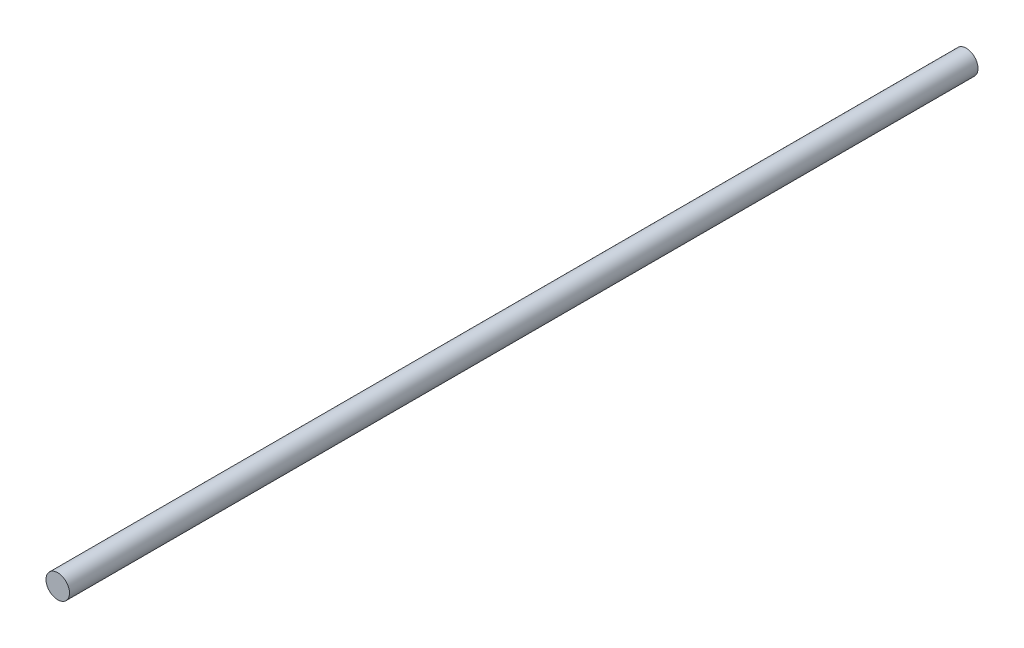
SolidWorks part; units mm, degrees
ref_plane "前视基准面" through (0, 0, 0) normal (0, 0, 1) x (1, 0, 0)
ref_plane "上视基准面" through (0, 0, 0) normal (0, 1, 0) x (1, 0, 0)
ref_plane "右视基准面" through (0, 0, 0) normal (1, 0, 0) x (0, 0, -1)
sketch "草图1" plane through (0, 0, 0) normal (0, 0, 1) x (1, 0, 0)
  circle A0 centre (0, 0) radius 3
  dimension "D1" = 6
extrude "凸台-拉伸1" add sketch "草图1" along normal blind 232
